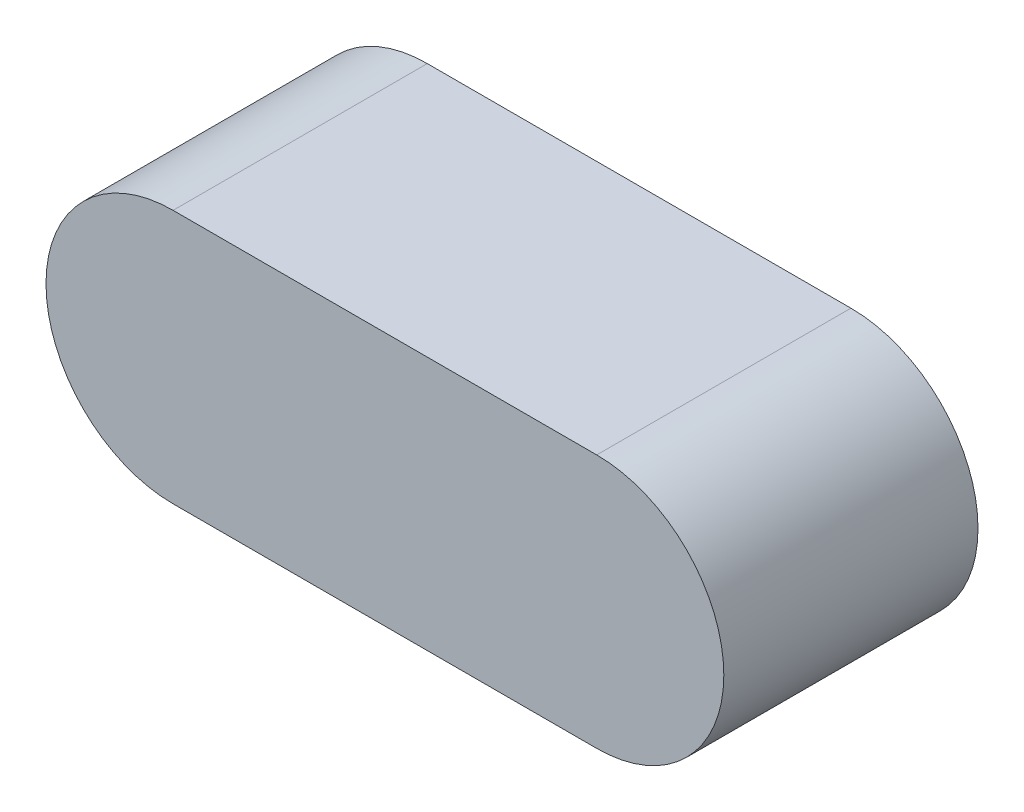
SolidWorks part; units mm, degrees
ref_plane "Płaszczyzna przednia" through (0, 0, 0) normal (0, 0, 1) x (1, 0, 0)
ref_plane "Płaszczyzna górna" through (0, 0, 0) normal (0, 1, 0) x (1, 0, 0)
ref_plane "Płaszczyzna prawa" through (0, 0, 0) normal (1, 0, 0) x (0, 0, -1)
sketch "Szkic1" plane through (0, 0, 0) normal (0, 0, 1) x (1, 0, 0)
  line L0 (0, 0) -> (5, 0) construction
  line L1 (0, 1.5) -> (5, 1.5)
  line L2 (0, -1.5) -> (5, -1.5)
  arc A0 (0, 1.5) -> (0, -1.5) centre (0, 0) ccw
  arc A1 (5, -1.5) -> (5, 1.5) centre (5, 0) ccw
  point P3 (2.5, 0)
  point P8 (-1.5, 0)
  point P9 (6.5, 0)
  dimension "D1" = 8
  dimension "3" = 3
extrude "Dodanie-wyciągnięcie1" add sketch "Szkic1" along normal mid plane 3
